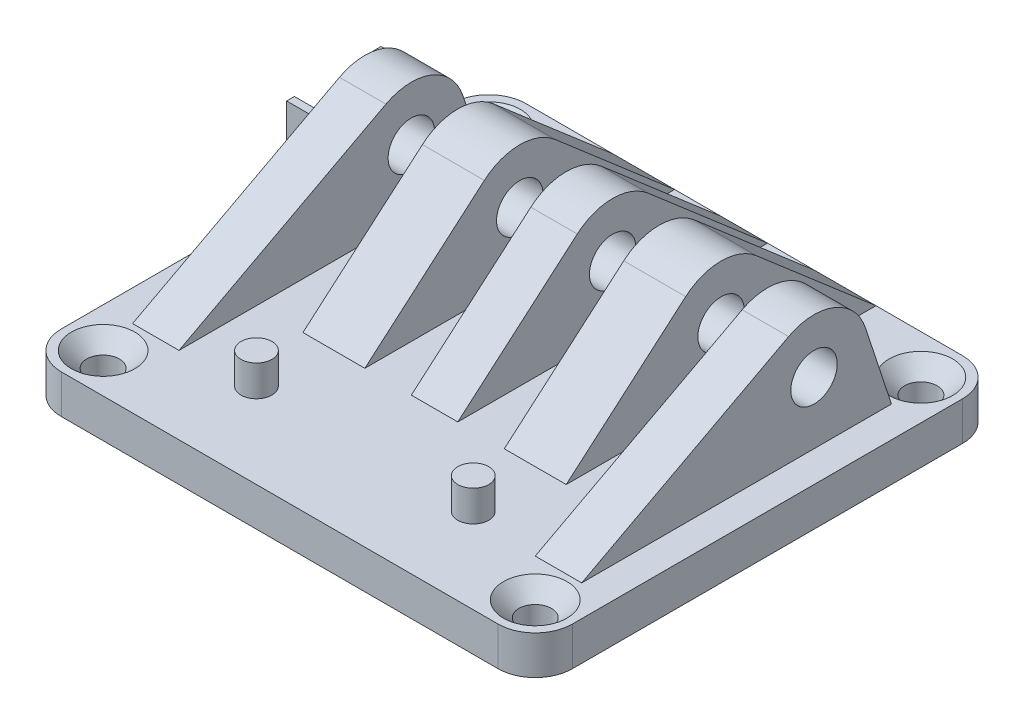
SolidWorks part; units mm, degrees
ref_plane "Front Plane" through (0, 0, 0) normal (0, 0, 1) x (1, 0, 0)
ref_plane "Top Plane" through (0, 0, 0) normal (0, 1, 0) x (1, 0, 0)
ref_plane "Right Plane" through (0, 0, 0) normal (1, 0, 0) x (0, 0, -1)
sketch "Sketch4" plane through (0, 0, 0) normal (0, 1, 0) x (1, 0, 0)
  line L0 (33, 60) -> (33, 0) construction
  line L1 (0, 0) -> (66, 0)
  line L2 (0, 0) -> (0, 60)
  line L3 (0, 60) -> (66, 60)
  line L4 (66, 0) -> (66, 60)
  line L6 (30, 20) -> (36, 20)
  line L7 (30, 20) -> (30, 60)
  line L8 (30, 60) -> (36, 60)
  line L9 (36, 20) -> (36, 60)
  line L10 (30, 20) -> (36, 60) construction
  line L11 (30, 60) -> (36, 20) construction
  line L12 (36, 60) -> (42, 60)
  line L13 (36, 60) -> (36, 20)
  line L14 (36, 20) -> (42, 20)
  line L15 (42, 60) -> (42, 20)
  line L16 (42, 20) -> (50, 20)
  line L17 (42, 20) -> (42, 60)
  line L18 (42, 60) -> (50, 60)
  line L19 (50, 20) -> (50, 60)
  line L20 (50, 60) -> (56, 60)
  line L21 (50, 60) -> (50, 20)
  line L22 (50, 20) -> (56, 20)
  line L23 (56, 60) -> (56, 20)
  line L24 (56, 50) -> (62, 50)
  line L25 (56, 50) -> (56, 10)
  line L26 (56, 10) -> (62, 10)
  line L27 (62, 50) -> (62, 10)
  point P7 (33, 40)
  point P22 (53, 20)
  dimension "D1" = 6
  dimension "D2" = 6
  dimension "D3" = 8
  dimension "D4" = 6
  dimension "D5" = 10
  dimension "D6" = 10
  dimension "D7" = 20
  dimension "D8" = 40
  dimension "D9" = 10
  dimension "D10" = 6
extrude "Boss-Extrude4" add sketch "Sketch4" along normal blind 5 contours L24 L27 L26 L25 L22 L16 L14 L6 L7 L3 L2 L1 L4 L23 | L15 L3 L9 L14 | L6 L9 L3 L7 | L16 L19 L3 L15 | L23 L3 L19 L22 | L27 L24 L23 L25 L26
sketch "Sketch6" plane through (0, 5, 0) normal (0, 1, 0) x (1, 0, 0)
  line L0 (42, 60) -> (50, 60) construction
  line L1 (50, 20) -> (50, 60) construction
  line L2 (50, 60) -> (56, 60) construction
  line L3 (56, 60) -> (56, 20) construction
  line L4 (66, 0) -> (66, 60)
  line L5 (66, 60) -> (0, 60)
  line L6 (0, 60) -> (0, 0)
  line L7 (0, 0) -> (66, 0)
  line L8 (66, 0) -> (66, 60)
  line L9 (66, 60) -> (0, 60)
  line L10 (0, 60) -> (0, 0)
  line L11 (0, 0) -> (66, 0)
  line L12 (50, 20) -> (56, 20) construction
  line L13 (50, 60) -> (50, 20) construction
  line L14 (42, 20) -> (50, 20) construction
  line L15 (36, 20) -> (42, 20) construction
  line L16 (42, 60) -> (42, 20) construction
  line L17 (42, 20) -> (42, 60) construction
  line L18 (36, 60) -> (42, 60) construction
  line L19 (30, 20) -> (36, 20) construction
  line L20 (30, 20) -> (30, 60) construction
  line L21 (30, 60) -> (36, 60) construction
  line L22 (36, 20) -> (36, 60) construction
  line L23 (36, 60) -> (36, 20) construction
  line L24 (0, 0) -> (66, 0) construction
  line L25 (66, 0) -> (66, 60) construction
  line L26 (0, 60) -> (66, 60) construction
  line L27 (0, 0) -> (0, 60) construction
  line L28 (56, 50) -> (62, 50) construction
  line L29 (62, 50) -> (62, 10) construction
  line L30 (56, 10) -> (62, 10) construction
  line L31 (56, 50) -> (56, 10) construction
  line L32 (42, 60) -> (50, 60)
  line L33 (50, 20) -> (50, 60)
  line L34 (50, 60) -> (56, 60)
  line L35 (56, 60) -> (56, 20)
  line L36 (50, 20) -> (56, 20)
  line L37 (50, 60) -> (50, 20)
  line L38 (42, 20) -> (50, 20)
  line L39 (36, 20) -> (42, 20)
  line L40 (42, 60) -> (42, 20)
  line L41 (42, 20) -> (42, 60)
  line L42 (36, 60) -> (42, 60)
  line L43 (30, 20) -> (36, 20)
  line L44 (30, 20) -> (30, 60)
  line L45 (30, 60) -> (36, 60)
  line L46 (36, 20) -> (36, 60)
  line L47 (36, 60) -> (36, 20)
  line L48 (0, 0) -> (66, 0)
  line L49 (66, 0) -> (66, 60)
  line L50 (0, 60) -> (66, 60)
  line L51 (0, 0) -> (0, 60)
  line L52 (56, 50) -> (62, 50)
  line L53 (62, 50) -> (62, 10)
  line L54 (56, 10) -> (62, 10)
  line L55 (56, 50) -> (56, 10)
  dimension "D1" = 0
extrude "Boss-Extrude5" add sketch "Sketch6" along normal blind 15 contours L43 L46 L9 L44 | L9 L40 L38 L33 | L35 L55 L54 L53 L52
sketch "Sketch7" plane through (30, 0, 0) normal (-1, 0, 0) x (0, 0, 1)
  line L0 (-40, 20) -> (-40, 5) construction
  line L1 (-20, 20) -> (-60, 20) construction
  line L2 (-20, 5) -> (-60, 5) construction
  circle A0 centre (-40, 13) radius 3
  point P8 (-40, 16)
  dimension "D1" = 6
  dimension "D2" = 4
extrude "Cut-Extrude2" cut sketch "Sketch7" against normal through all
sketch "Sketch8" plane through (30, 0, 0) normal (-1, 0, 0) x (0, 0, 1)
  line L0 (-20, 5) -> (-35.4293, 18.3018)
  line L1 (-40, 21) -> (-40, 5) construction
  line L2 (-60, 5) -> (-44.5707, 18.3018)
  line L4 (-60, 5) -> (-20, 5)
  line L5 (-20, 5) -> (-20, 20)
  line L6 (-20, 20) -> (-60, 20)
  line L7 (-60, 20) -> (-60, 5)
  line L8 (-60, 5) -> (-20, 5)
  line L9 (-20, 5) -> (-20, 20)
  line L10 (-20, 20) -> (-60, 20)
  line L11 (-60, 20) -> (-60, 5)
  circle A0 centre (-40, 13) radius 3 construction
  circle A1 centre (-40, 13) radius 3
  arc A2 (-44.5707, 18.3018) -> (-35.4293, 18.3018) centre (-40, 13) cw
  line M10 (-20, 5) -> (-20, 20)
  line M11 (-20, 20) -> (-60, 20)
  line M12 (-60, 20) -> (-60, 5)
  dimension "D1" = 0
extrude "Cut-Extrude3" cut sketch "Sketch8" against normal up to surface (20 mm away) contours L2 A2 L10 M12 | A2 L0 M11 M10 up to face at (50, 13, -37)
sketch "Sketch9" plane through (62, 0, 0) normal (1, 0, 0) x (0, 0, -1)
  line L0 (46.6496, 15.187) -> (50, 5)
  line L1 (10, 5) -> (36.7179, 19.1829)
  line L4 (10, 5) -> (50, 5)
  line L5 (50, 5) -> (50, 20)
  line L6 (50, 20) -> (10, 20)
  line L7 (10, 20) -> (10, 5)
  line L8 (10, 5) -> (50, 5)
  line L9 (50, 5) -> (50, 20)
  line L10 (50, 20) -> (10, 20)
  line L11 (10, 20) -> (10, 5)
  circle A0 centre (40, 13) radius 3 construction
  circle A1 centre (40, 13) radius 3
  arc A2 (40, 20) -> (46.6496, 15.187) centre (40, 13) cw
  arc A3 (40, 20) -> (36.7179, 19.1829) centre (40, 13) ccw
  line M9 (50, 5) -> (50, 20)
  line M10 (50, 20) -> (10, 20)
  line M11 (10, 20) -> (10, 5)
  dimension "D1" = 0
extrude "Cut-Extrude4" cut sketch "Sketch9" against normal up to next contours A3 L10 L1 M11 | A2 L0 M10 M9
ref_plane "Plane1" through (33, 0, 0) normal (-1, 0, 0) x (0, 0, 1)
mirror "Mirror1" about plane through (33, 0, 0) normal (-1, 0, 0) of "Cut-Extrude4", "Cut-Extrude3", "Cut-Extrude2", "Boss-Extrude5"
sketch "Sketch10" plane through (0, 5, 0) normal (0, 1, 0) x (1, 0, 0)
  line L0 (33, 60) -> (33, 0) construction
  line L1 (60.9, 5.1) -> (5.1, 5.1) construction
  line L2 (60.9, 5.1) -> (60.9, 54.9) construction
  line L3 (60.9, 54.9) -> (5.1, 54.9) construction
  line L4 (5.1, 5.1) -> (5.1, 54.9) construction
  line L5 (60.9, 5.1) -> (5.1, 54.9) construction
  line L6 (60.9, 54.9) -> (5.1, 5.1) construction
  line L9 (0, 60) -> (66, 60) construction
  line L10 (0, 0) -> (0, 60) construction
  circle A0 centre (5.1, 54.9) radius 2.1
  circle A1 centre (60.9, 54.9) radius 2.1
  circle A2 centre (60.9, 5.1) radius 2.1
  circle A3 centre (5.1, 5.1) radius 2.1
  point P0 (33, 30)
  point P9 (5.1, 57)
  point P10 (3, 54.9)
  dimension "D3" = 4.2
  dimension "D1" = 3
  dimension "D2" = 3
extrude "Cut-Extrude5" cut sketch "Sketch10" against normal up to next
chamfer "Chamfer1" distance 2 angle 45 4 edges at (5.1, 5, -3) (60.9, 5, -3) (60.9, 5, -52.8) (5.1, 5, -52.8)
fillet "Fillet1" radius 4.8 4 edges at (66, 2.5, 0) (0, 2.5, 0) (66, 2.5, -60) (0, 2.5, -60)
sketch "Sketch11" plane through (0, 5, 0) normal (0, 1, 0) x (1, 0, 0)
  line L1 (36, 37) -> (36, 43) construction
  line L2 (36, 37) -> (36, 43)
  line L3 (33, 11) -> (33, -11) construction
  circle A0 centre (47, 11) radius 2
  circle A1 centre (19, 11) radius 2
  point P4 (36, 40)
  dimension "D1" = 4
  dimension "D3" = 28
  dimension "D2" = 29
extrude "Boss-Extrude6" add sketch "Sketch11" along normal blind 4 contours A1 | A0
sketch "Sketch12" plane through (4, 0, 0) normal (-1, 0, 0) x (0, 0, 1)
  line L0 (-45.1, 15.9445) -> (-46.1, 15.9445)
  line L1 (-34.9, 15.9445) -> (-40, 18.889)
  line L2 (-40, 18.889) -> (-45.1, 15.9445)
  line L3 (-45.1, 15.9445) -> (-45.1, 10.0555)
  line L4 (-45.1, 10.0555) -> (-40, 7.111)
  line L5 (-40, 7.111) -> (-34.9, 10.0555)
  line L6 (-34.9, 10.0555) -> (-34.9, 15.9445)
  line L7 (-46.1, 15.9445) -> (-46.1, 5)
  line L8 (-50, 5) -> (-10, 5) construction
  line L9 (-34.9, 15.9445) -> (-33.9, 15.9445)
  line L10 (-33.9, 15.9445) -> (-33.9, 5)
  line L11 (-46.1, 5) -> (-33.9, 5)
  line L12 (-46.1, 15.9445) -> (-45.1, 15.9445)
  line L13 (-34.9, 15.9445) -> (-33.9, 15.9445)
  circle A0 centre (-40, 13) radius 3 construction
  circle A1 centre (-40, 13) radius 3
  circle A2 centre (-40, 13) radius 5.1 construction
  line M12 (-50, 5) -> (-10, 5)
  dimension "D1" = 10.2
  dimension "D2" = 1
extrude "Boss-Extrude7" add sketch "Sketch12" along normal up to surface (4 mm away) contours L10 L9 L6 L5 L4 L3 L0 L7 M12 up to face at (0, 2.5, -30)
